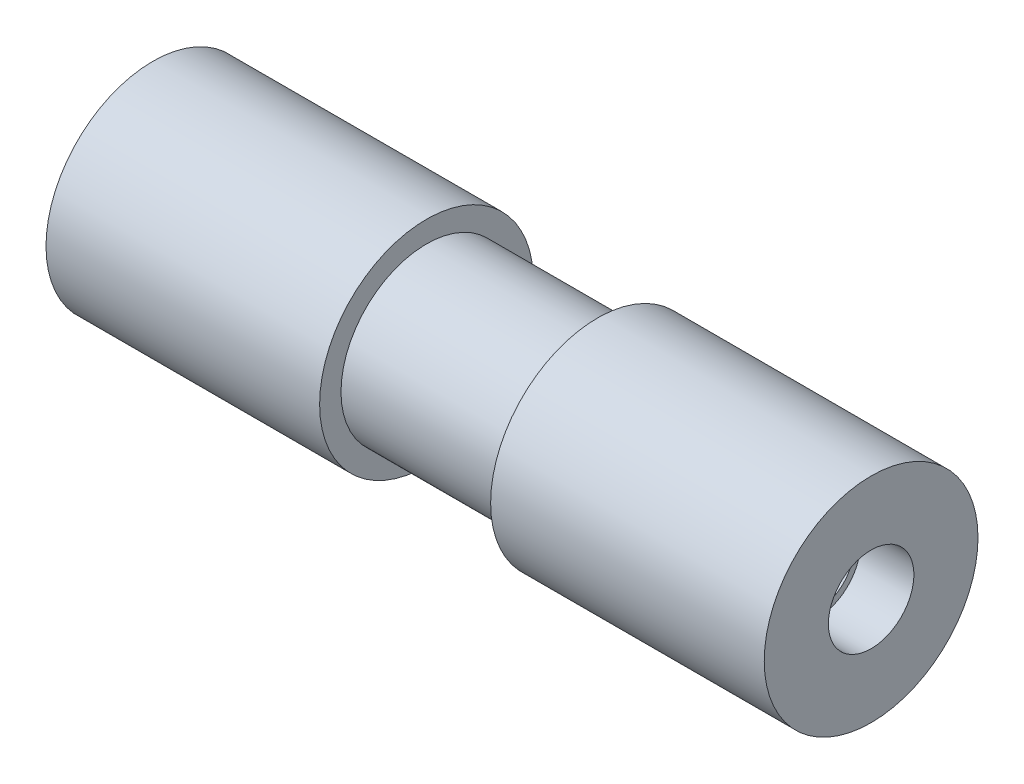
SolidWorks part; units mm, degrees
material "Nylon 101"
ref_plane "Front Plane" through (0, 0, 0) normal (0, 0, 1) x (1, 0, 0)
ref_plane "Top Plane" through (0, 0, 0) normal (0, 1, 0) x (1, 0, 0)
ref_plane "Right Plane" through (0, 0, 0) normal (1, 0, 0) x (0, 0, -1)
sketch "Sketch1" plane through (0, 0, 0) normal (1, 0, 0) x (0, 0, -1)
  circle A0 centre (0, 0) radius 31.75
  circle A1 centre (0, 0) radius 10.795
  dimension "D2" = 63.5
  dimension "D1" = 20.955
extrude "Boss-Extrude1" add sketch "Sketch1" along normal blind 106.68
sketch "Sketch2" plane through (0, 0, 0) normal (-1, 0, 0) x (0, 0, 1)
  circle A0 centre (0, 0) radius 12.7
extrude "Cut-Extrude1" cut sketch "Sketch2" against normal blind 15.875
mirror "Mirror1" about plane through (106.68, 0, 0) normal (1, 0, 0) of "Cut-Extrude1", "Boss-Extrude1"
sketch "Sketch3" plane through (0, 0, 0) normal (-1, 0, 0) x (0, 0, 1)
  circle A0 centre (0, 0) radius 25.4
  dimension "D1" = 50.8
extrude "Cut-Extrude2" cut sketch "Sketch3" against normal blind 50.8 from offset 81.28 flip side to cut
